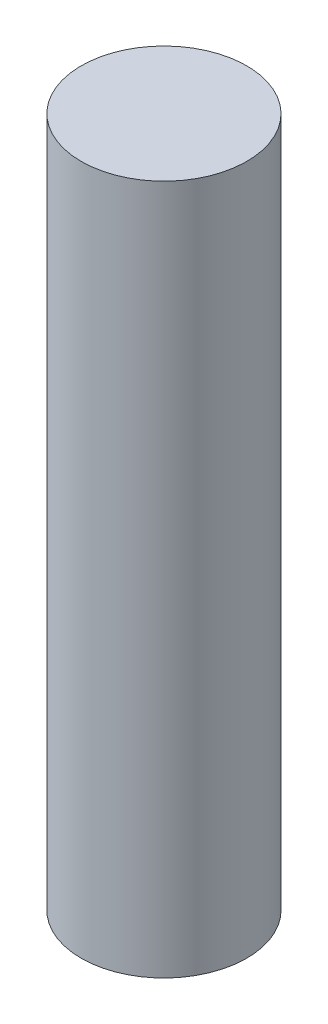
SolidWorks part; units mm, degrees
ref_plane "Front Plane" through (0, 0, 0) normal (0, 0, 1) x (1, 0, 0)
ref_plane "Top Plane" through (0, 0, 0) normal (0, 1, 0) x (1, 0, 0)
ref_plane "Right Plane" through (0, 0, 0) normal (1, 0, 0) x (0, 0, -1)
sketch "Sketch2" plane through (0, 0, 0) normal (0, 1, 0) x (1, 0, 0)
  circle A0 centre (0, 0) radius 6
  dimension "D1" = 12
extrude "Boss-Extrude1" add sketch "Sketch2" along normal blind 50
